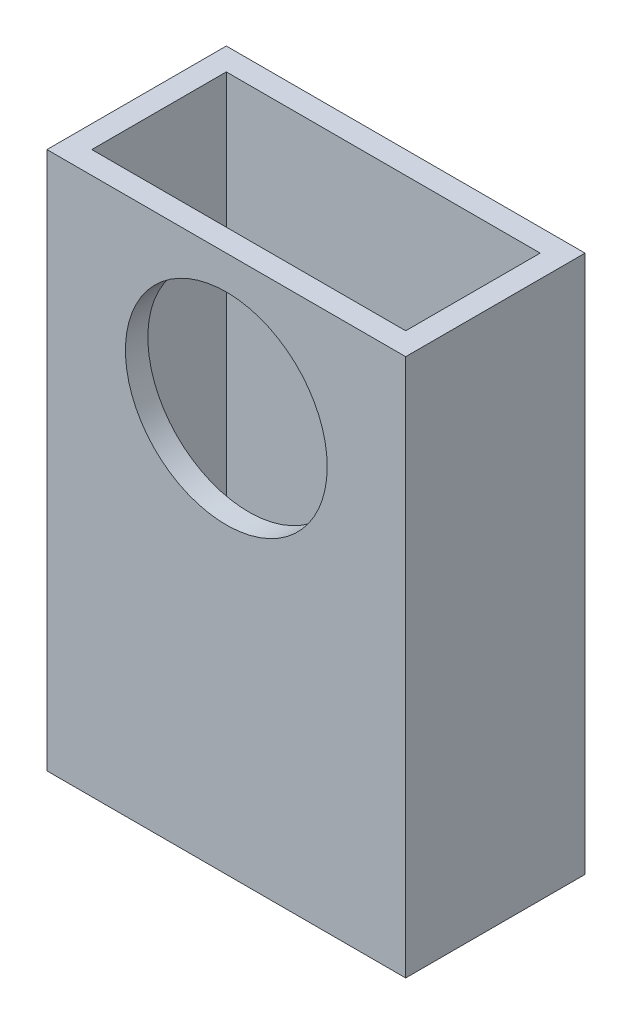
SolidWorks part; units mm, degrees
ref_plane "Front Plane" through (0, 0, 0) normal (0, 0, 1) x (1, 0, 0)
ref_plane "Top Plane" through (0, 0, 0) normal (0, 1, 0) x (1, 0, 0)
ref_plane "Right Plane" through (0, 0, 0) normal (1, 0, 0) x (0, 0, -1)
sketch "Sketch1" plane through (0, 0, 0) normal (0, 0, 1) x (1, 0, 0)
  line L1 (0, 0) -> (50.8, 0)
  line L2 (0, 0) -> (0, 76.2)
  line L3 (0, 76.2) -> (50.8, 76.2)
  line L4 (50.8, 0) -> (50.8, 76.2)
  dimension "D1" = 50.8
  dimension "D2" = 76.2
extrude "Boss-Extrude1" add sketch "Sketch1" along normal blind 25.4
sketch "Sketch2" plane through (0, 0, 0) normal (0, -1, 0) x (1, 0, 0)
  line L0 (0, 25.4) -> (50.8, 25.4) construction
  line L1 (3.175, 22.225) -> (47.625, 22.225)
  line L2 (3.175, 22.225) -> (3.175, 3.175)
  line L3 (3.175, 3.175) -> (47.625, 3.175)
  line L4 (47.625, 22.225) -> (47.625, 3.175)
  line L5 (50.8, 25.4) -> (50.8, 0) construction
  line L6 (0, 0) -> (50.8, 0) construction
  line L7 (0, 25.4) -> (0, 0) construction
  point P12 (0, 12.7)
  dimension "D1" = 3.175
  dimension "D2" = 3.175
  dimension "D3" = 3.175
  dimension "D4" = 3.175
extrude "Cut-Extrude1" cut sketch "Sketch2" against normal through all
sketch "Sketch3" plane through (0, 0, 25.4) normal (0, 0, 1) x (1, 0, 0)
  line L0 (50.8, 76.2) -> (0, 76.2) construction
  circle A0 centre (25.4, 57.15) radius 14.2875
  dimension "D1" = 28.575
  dimension "D2" = 19.05
extrude "Cut-Extrude2" cut sketch "Sketch3" against normal blind 11.2767
